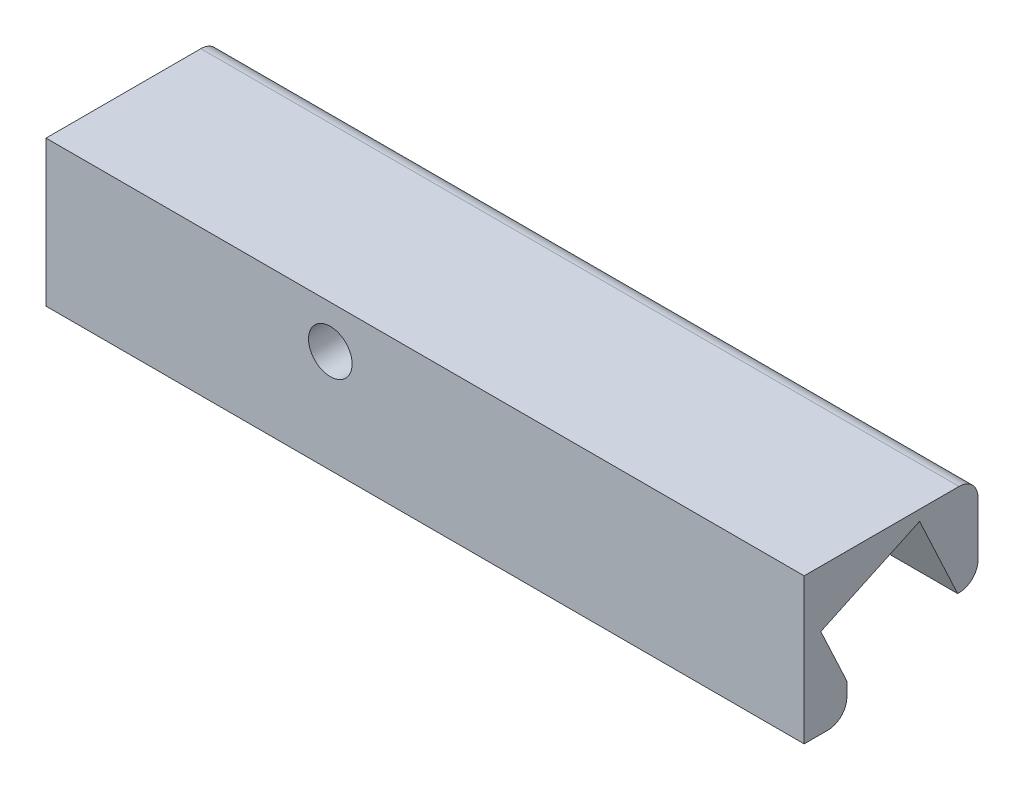
SolidWorks part; units mm, degrees
ref_plane "Front Plane" through (0, 0, 0) normal (0, 0, 1) x (1, 0, 0)
ref_plane "Top Plane" through (0, 0, 0) normal (0, 1, 0) x (1, 0, 0)
ref_plane "Right Plane" through (0, 0, 0) normal (1, 0, 0) x (0, 0, -1)
sketch "Sketch1" plane through (0, 0, 0) normal (1, 0, 0) x (0, 0, -1)
  line L0 (0, 0) -> (2.4995, 0)
  line L2 (18.3407, 7.6355) -> (18.3407, 13.3601)
  line L3 (16.3407, 15.3601) -> (0, 15.3601)
  line L4 (0, 15.3601) -> (0, 0)
  line L6 (16.1904, 5.6412) -> (14.9225, 8.3601)
  line L7 (14.9225, 8.3601) -> (4.5, 3.5)
  line L8 (4.5, 3.5) -> (4.5, 2.0005)
  arc A0 (16.3407, 15.3601) -> (18.3407, 13.3601) centre (16.3407, 13.3601) cw
  arc A1 (16.1904, 5.6412) -> (18.3407, 7.6355) centre (16.3407, 7.6355) ccw
  arc A2 (2.4995, 0) -> (4.5, 2.0005) centre (2.4995, 2.0005) ccw
  dimension "D7" = 4
  dimension "D4" = 4
  dimension "D8" = 4.0011
  dimension "D3" = 11.5
  dimension "D1" = 4.5
  dimension "D5" = 7
  dimension "D6" = 3
extrude "ProfileBoss-Extrude1" add sketch "Sketch1" along normal blind 80
sketch "Sketch2" plane through (0, 1.1513, 0.5368) normal (0, -0.9063, -0.4226) x (1, 0, 0)
  line L0 (80, -5.5575) -> (80, -17.0575) construction
  line L1 (0, -5.5575) -> (0, -17.0575) construction
  line L2 (80, -5.5575) -> (0, -5.5575) construction
  circle A0 centre (43.85, -11.3075) radius 2.3
  dimension "D1" = 4.6
  dimension "D2" = 5.75
  dimension "D3" = 36.15
  dimension "D4" = 43.85
extrude "LedStripMountHolesCut-Extrude1" cut sketch "Sketch2" against normal blind 4.5
sketch "Sketch4" plane through (0, 1.1513, 0.5368) normal (0, -0.9063, -0.4226) x (1, 0, 0)
  line L0 (80, -5.5575) -> (80, -17.0575) construction
  line L5 (80, -17.0575) -> (0, -17.0575) construction
  line L6 (52, -5.5575) -> (80, -5.5575)
  line L7 (52, -5.5575) -> (52, -17.0575)
  line L8 (52, -17.0575) -> (80, -17.0575)
  line L9 (80, -5.5575) -> (80, -17.0575)
  dimension "D2" = 28
extrude "PowerConnectorCut-Extrude4" cut sketch "Sketch4" against normal blind 6.5
sketch "Sketch3" plane through (0, 0, 0) normal (0, 0, 1) x (1, 0, 0)
  line L1 (80, 15.3601) -> (80, 0) construction
  circle A0 centre (30, 10.8601) radius 2.3
  dimension "D1" = 4.6
  dimension "D4" = 4.5
  dimension "D2" = 50
extrude "MountingHolesCut-Extrude3" cut sketch "Sketch3" against normal blind 4.5
equation "\"LightStripShortLength\"= 80mm"
equation "\"D1@ProfileBoss-Extrude1\"=\"LightStripShortLength\""
equation "\"LightStripWidth\"= 11.5mm'Spec"
equation "\"D3@Sketch1\"=\"LightStripWidth\""
equation "\"D2@Sketch2\"=\"LightStripWidth\"/2"
equation "\"LightStripMountHoleFromLeftOrRightEdge\"= ( \"LightStipLength\" - \"LightStripDistanceBetweenMountingHoles\" ) / 2"
equation "\"LightStripGuideMountingHoleFromLeftOrRightSide\"= 50mm"
equation "\"D3@Sketch2\"=\"LightStripMountHoleFromLeftOrRightEdge\""
equation "\"D2@Sketch3\"=\"LightStripGuideMountingHoleFromLeftOrRightSide\""
equation "\"LightStripGuideMountingHoleFromTop\"=4.5"
equation "\"D4@Sketch3\"=\"LightStripGuideMountingHoleFromTop\""
equation "\"LightStipLength\"= 270mm'From Step file"
equation "\"LightStripDistanceBetweenMountingHoles\"= 197.7mm'From Step file"
